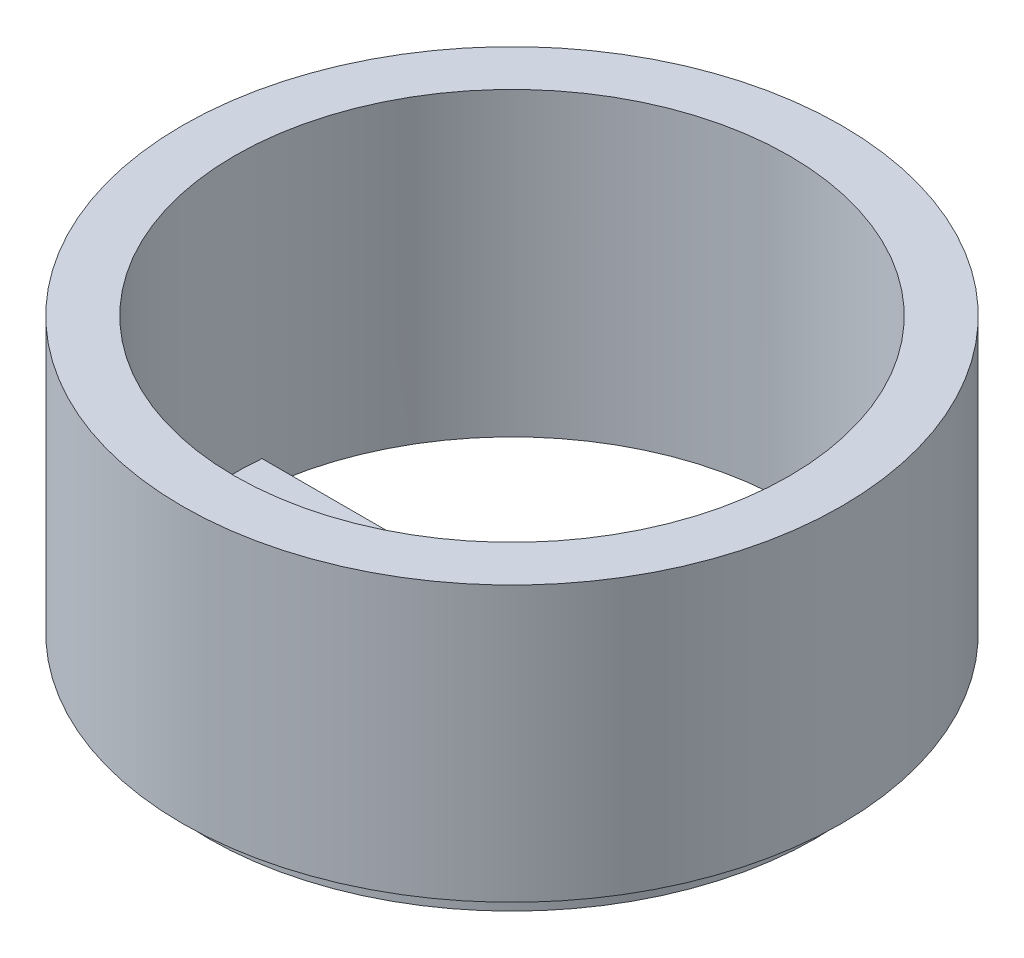
SolidWorks part; units mm, degrees
ref_plane "Front Plane" through (0, 0, 0) normal (0, 0, 1) x (1, 0, 0)
ref_plane "Top Plane" through (0, 0, 0) normal (0, 1, 0) x (1, 0, 0)
ref_plane "Right Plane" through (0, 0, 0) normal (1, 0, 0) x (0, 0, -1)
sketch "Sketch1" plane through (0, 0, 0) normal (0, 0, 1) x (1, 0, 0)
  line L0 (0, 0) -> (0, 50.8481) construction
  line L2 (33.655, 36.5125) -> (40.005, 36.5125)
  line L3 (40.005, 36.5125) -> (40.005, 3.175)
  line L4 (40.005, 3.175) -> (36.83, 3.175)
  line L5 (36.83, 3.175) -> (36.83, 0)
  line L6 (36.83, 0) -> (33.655, 0)
  line L7 (33.655, 36.5125) -> (33.655, 3.175)
  line L8 (33.655, 3.175) -> (0, 3.175)
  line L9 (0, 3.175) -> (0, 0)
  line L10 (0, 0) -> (33.655, 0)
  point P5 (38.4175, 3.175)
  dimension "D1" = 33.3375
  dimension "D2" = 3.175
  dimension "D3" = 36.83
  dimension "D4" = 40.005
  dimension "D5" = 6.35
  dimension "D6" = 3.175
revolve "Revolve1" add sketch "Sketch1" angle 360 about L0
sketch "Sketch2" plane through (0, 3.175, 0) normal (0, 1, 0) x (1, 0, 0)
  line L0 (-33.5049, 3.175) -> (33.5049, 3.175)
  line L1 (-33.5049, -3.175) -> (33.5049, -3.175)
  line L2 (0, 3.175) -> (0, -3.175) construction
  circle A0 centre (0, 0) radius 33.655 construction
  arc A1 (33.5049, 3.175) -> (-33.5049, 3.175) centre (0, 0) ccw
  circle A2 centre (0, 0) radius 33.655 construction
  arc A3 (-33.5049, -3.175) -> (33.5049, -3.175) centre (0, 0) ccw
  dimension "D1" = 6.35
extrude "Cut-Extrude1" cut sketch "Sketch2" against normal through all
